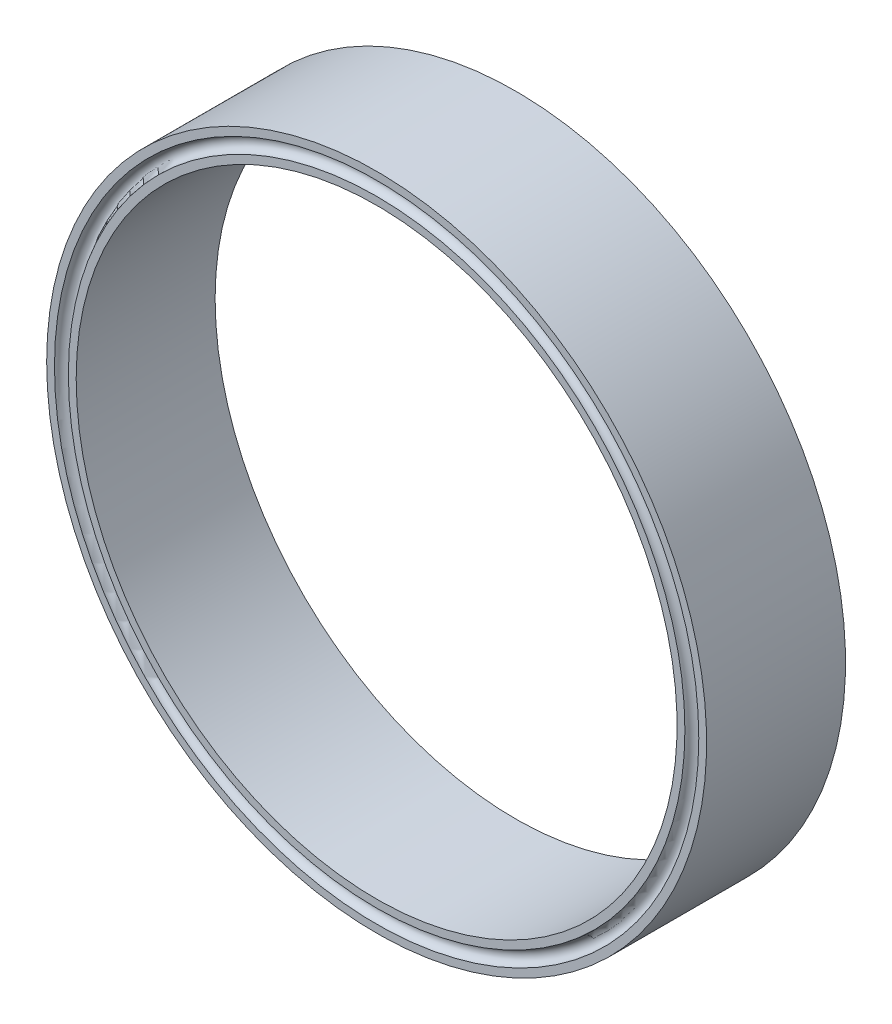
SolidWorks part; units mm, degrees
ref_plane "Front Plane" through (0, 0, 0) normal (0, 0, 1) x (1, 0, 0)
ref_plane "Top Plane" through (0, 0, 0) normal (0, 1, 0) x (1, 0, 0)
ref_plane "Right Plane" through (0, 0, 0) normal (1, 0, 0) x (0, 0, -1)
sketch "Sketch1" plane through (0, 0, 0) normal (0, 1, 0) x (1, 0, 0)
  line L0 (23.75, 10) -> (19.5, 10)
  line L1 (-23.75, 10) -> (23.75, 10) construction
  line L2 (-23.75, 10) -> (-23.75, -10) construction
  line L3 (-23.75, -10) -> (23.75, -10) construction
  line L4 (23.75, 10) -> (23.75, -10)
  line L5 (-23.75, 10) -> (23.75, -10) construction
  line L6 (-23.75, -10) -> (23.75, 10) construction
  line L7 (19.5, 10) -> (19.5, -10)
  line L8 (19.5, -10) -> (23.75, -10)
  circle A0 centre (21.625, 10) radius 1
  circle A1 centre (21.625, -10) radius 1
  point P0 (0, 0)
  dimension "D3" = 2
  dimension "D5" = 2
  dimension "D1" = 20
  dimension "D2" = 47.5
  dimension "D4" = 4.25
revolve "Revolve1" add sketch "Sketch1" angle 360 about L2
